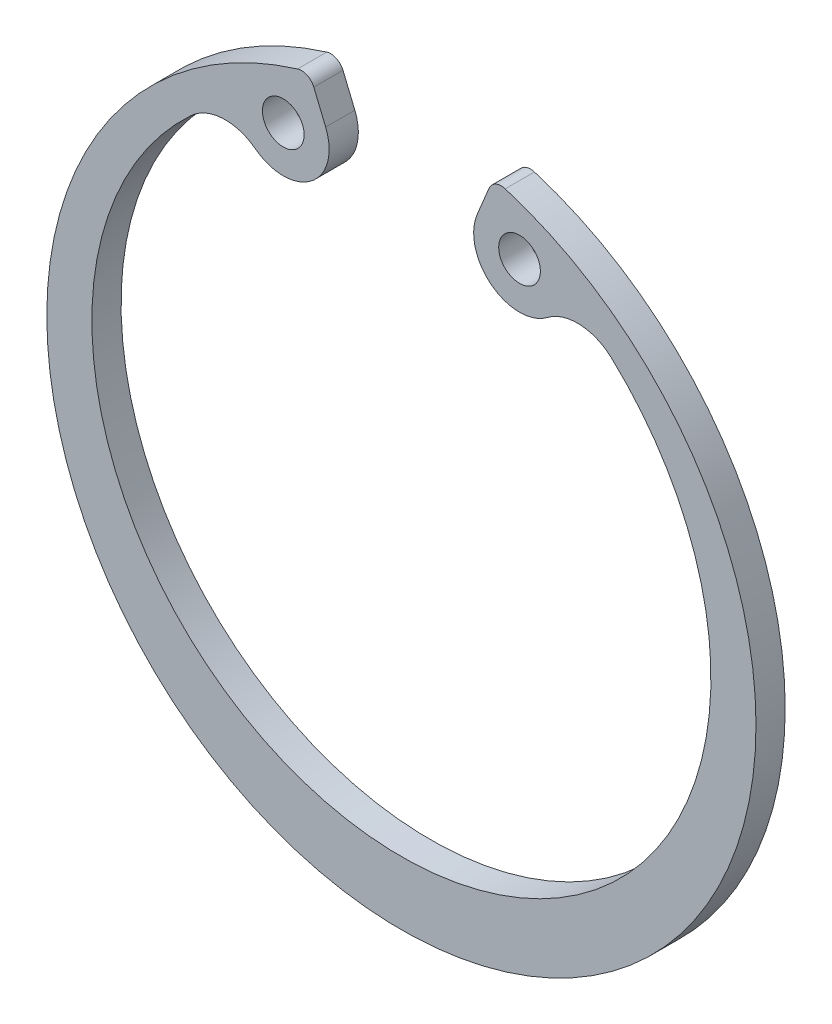
SolidWorks part; units mm, degrees
material "ASTM A36 Steel"
ref_plane "Alzado" through (0, 0, 0) normal (0, 0, 1) x (1, 0, 0)
ref_plane "Planta" through (0, 0, 0) normal (0, 1, 0) x (1, 0, 0)
ref_plane "Vista lateral" through (0, 0, 0) normal (1, 0, 0) x (0, 0, -1)
ref_plane "Plano1" through (0, 0, 1.75) normal (0, 0, 1) x (1, 0, 0)
sketch "Croquis1" plane through (0, 0, 1.75) normal (0, 0, 1) x (1, 0, 0)
  line L0 (5.2494, 19.8597) -> (4.5388, 18.1442)
  line L1 (-4.5388, 18.1442) -> (-5.2494, 19.8597)
  circle A0 centre (-7.0795, 17.0918) radius 1.25
  arc A1 (-6.2228, 20.3185) -> (6.2228, 20.3185) centre (0, 0) ccw
  arc A2 (6.2228, 20.3185) -> (5.2494, 19.8597) centre (5.9885, 19.5535) ccw
  arc A3 (4.5388, 18.1442) -> (8.744, 14.9028) centre (7.0795, 17.0918) ccw
  arc A4 (8.744, 14.9028) -> (12.597, 14.7168) centre (10.5597, 12.5147) cw
  arc A5 (12.597, 14.7168) -> (-12.597, 14.7168) centre (0, 1.1) cw
  arc A6 (-12.597, 14.7168) -> (-8.744, 14.9028) centre (-10.5597, 12.5147) cw
  arc A7 (-8.744, 14.9028) -> (-4.5388, 18.1442) centre (-7.0795, 17.0918) ccw
  arc A8 (-5.2494, 19.8597) -> (-6.2228, 20.3185) centre (-5.9885, 19.5535) ccw
  circle A9 centre (7.0795, 17.0918) radius 1.25
extrude "Saliente-Extruir1" add sketch "Croquis1" against normal blind 1.75
